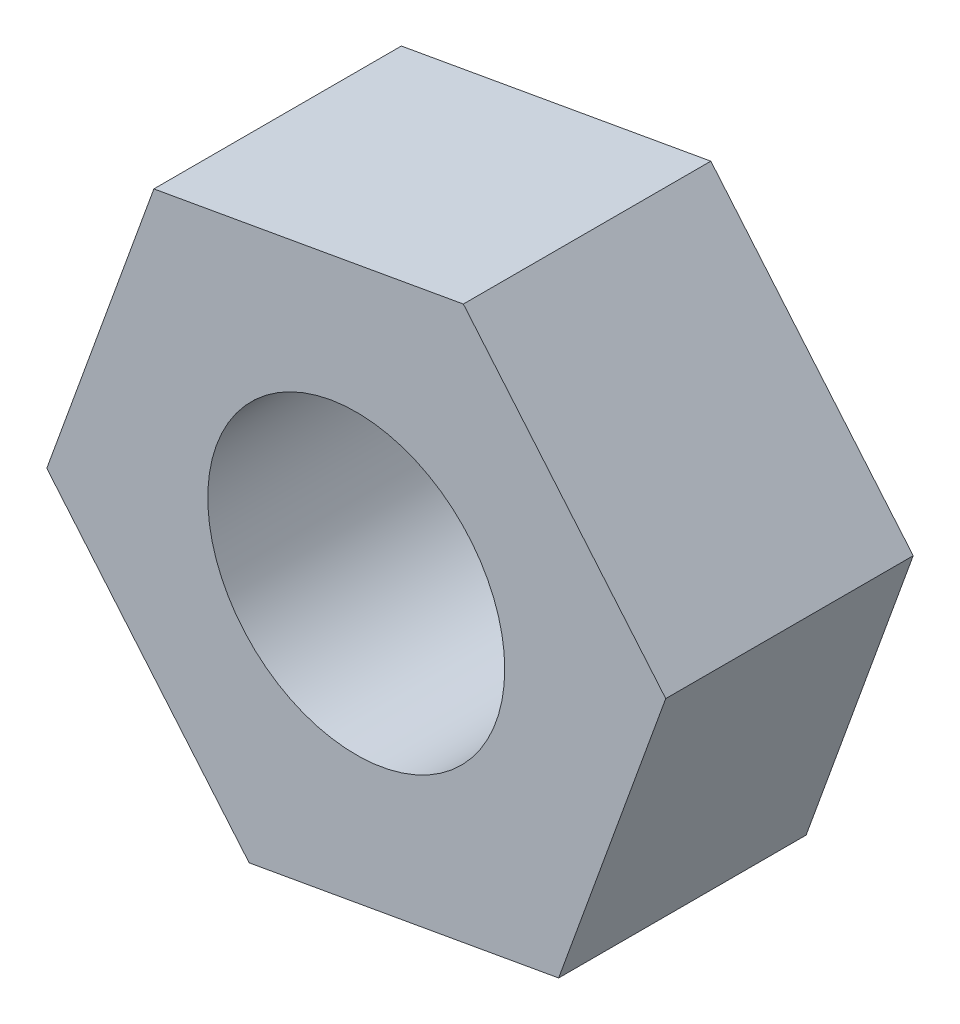
SolidWorks part; units mm, degrees
ref_plane "Front Plane" through (0, 0, 0) normal (0, 0, 1) x (1, 0, 0)
ref_plane "Top Plane" through (0, 0, 0) normal (0, 1, 0) x (1, 0, 0)
ref_plane "Right Plane" through (0, 0, 0) normal (1, 0, 0) x (0, 0, -1)
sketch "Sketch1" plane through (0, 0, 0) normal (0, 0, 1) x (1, 0, 0)
  line L1 (2.0445, -2.4297) -> (3.1264, 0.5557)
  line L2 (3.1264, 0.5557) -> (1.0819, 2.9854)
  line L3 (1.0819, 2.9854) -> (-2.0445, 2.4297)
  line L4 (-2.0445, 2.4297) -> (-3.1264, -0.5557)
  line L5 (-3.1264, -0.5557) -> (-1.0819, -2.9854)
  line L6 (-1.0819, -2.9854) -> (2.0445, -2.4297)
  circle A0 centre (0, 0) radius 2.75 construction
  circle A1 centre (0, 0) radius 1.5
  dimension "D2" = 3
  dimension "D1" = 5.5
extrude "Boss-Extrude1" add sketch "Sketch1" along normal blind 2.5
